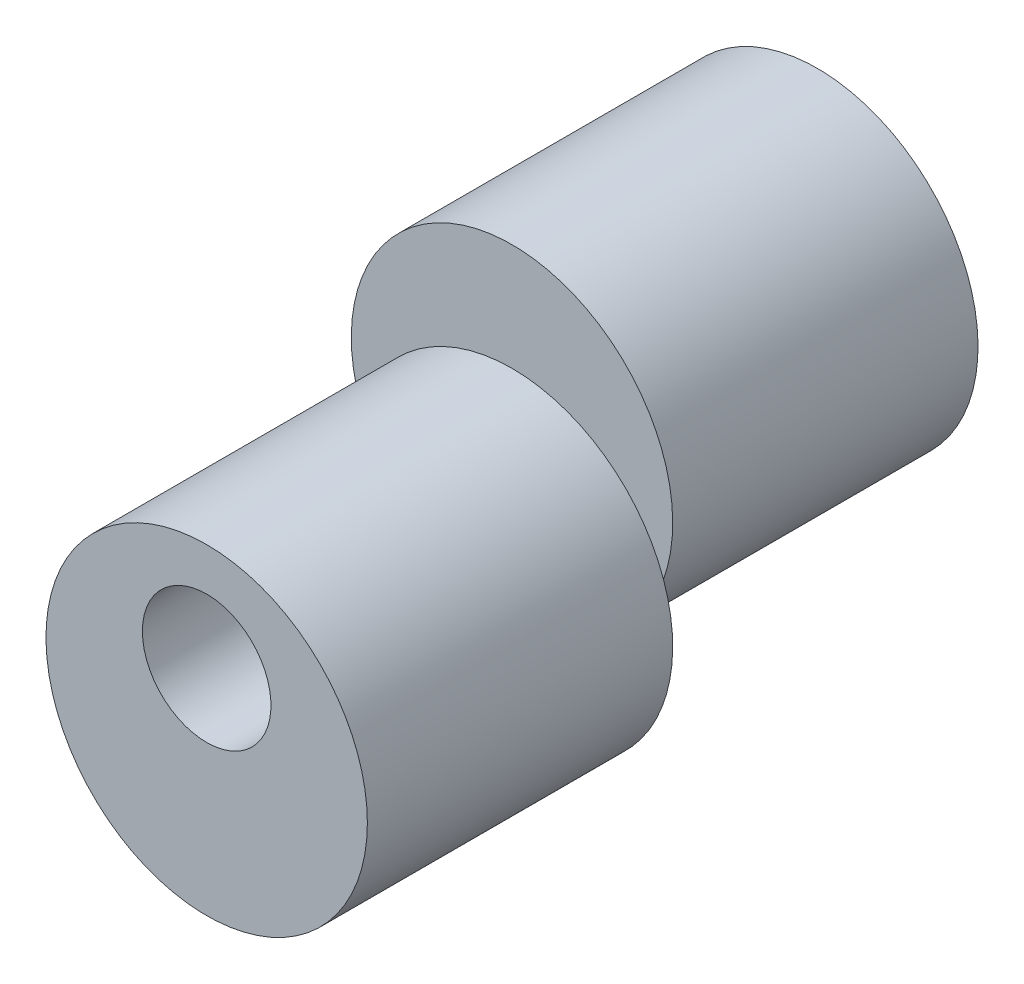
SolidWorks part; units mm, degrees
ref_plane "Front Plane" through (0, 0, 0) normal (0, 0, 1) x (1, 0, 0)
ref_plane "Top Plane" through (0, 0, 0) normal (0, 1, 0) x (1, 0, 0)
ref_plane "Right Plane" through (0, 0, 0) normal (1, 0, 0) x (0, 0, -1)
sketch "Sketch1" plane through (0, 0, 0) normal (0, 0, 1) x (1, 0, 0)
  circle A0 centre (0, 0) radius 7.5 construction
  circle A1 centre (0, -2.5) radius 7.5
  dimension "D1" = 15
  dimension "D2" = 2.5
extrude "Boss-Extrude1" add sketch "Sketch1" along normal blind 14.25
sketch "Sketch2" plane through (0, 0, 0) normal (0, 0, -1) x (-1, 0, 0)
  circle A0 centre (0, 2.5) radius 7.5
  circle A1 centre (0, -2.5) radius 7.5 construction
  dimension "D1" = 2.5
extrude "Boss-Extrude2" add sketch "Sketch2" along normal blind 14.25
sketch "Sketch3" plane through (0, 0, -14.25) normal (0, 0, -1) x (-1, 0, 0)
  circle A0 centre (0, 0) radius 3
  dimension "D1" = 6
extrude "Cut-Extrude1" cut sketch "Sketch3" against normal through all
